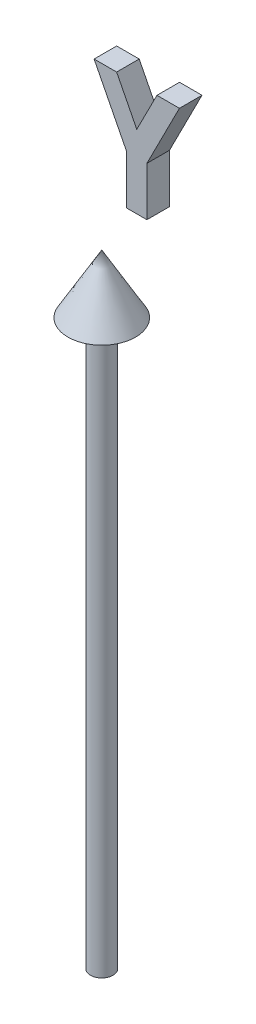
SolidWorks part; units mm, degrees
ref_plane "Front Plane" through (0, 0, 0) normal (0, 0, 1) x (1, 0, 0)
ref_plane "Top Plane" through (0, 0, 0) normal (0, 1, 0) x (1, 0, 0)
ref_plane "Right Plane" through (0, 0, 0) normal (1, 0, 0) x (0, 0, -1)
sketch "Sketch1" plane through (0, 0, 0) normal (0, 1, 0) x (1, 0, 0)
  circle A0 centre (0, 0) radius 1
  dimension "D1" = 2
extrude "Boss-Extrude1" add sketch "Sketch1" along normal blind 50
sketch "Sketch2" plane through (0, 0, 0) normal (0, 0, 1) x (1, 0, 0)
  line L0 (0, 50) -> (-3, 50)
  line L1 (1, 50) -> (-1, 50) construction
  line L2 (-3, 50) -> (0, 55.1962)
  line L3 (0, 55.1962) -> (0, 50)
  dimension "D1" = 3
  dimension "D2" = 60
revolve "Revolve1" add sketch "Sketch2" angle 360 about L3
sketch "Sketch3" plane through (0, 0, 0) normal (0, 0, 1) x (1, 0, 0)
  line L0 (0, 55.1962) -> (6.858, 55.1962) construction
  line L2 (0, 60.5151) -> (6.858, 60.5151) construction
  text T0 "<b>Y</b>" font "Century Gothic" height 10
extrude "Boss-Extrude2" add sketch "Sketch3" along normal mid plane 2 separate body
